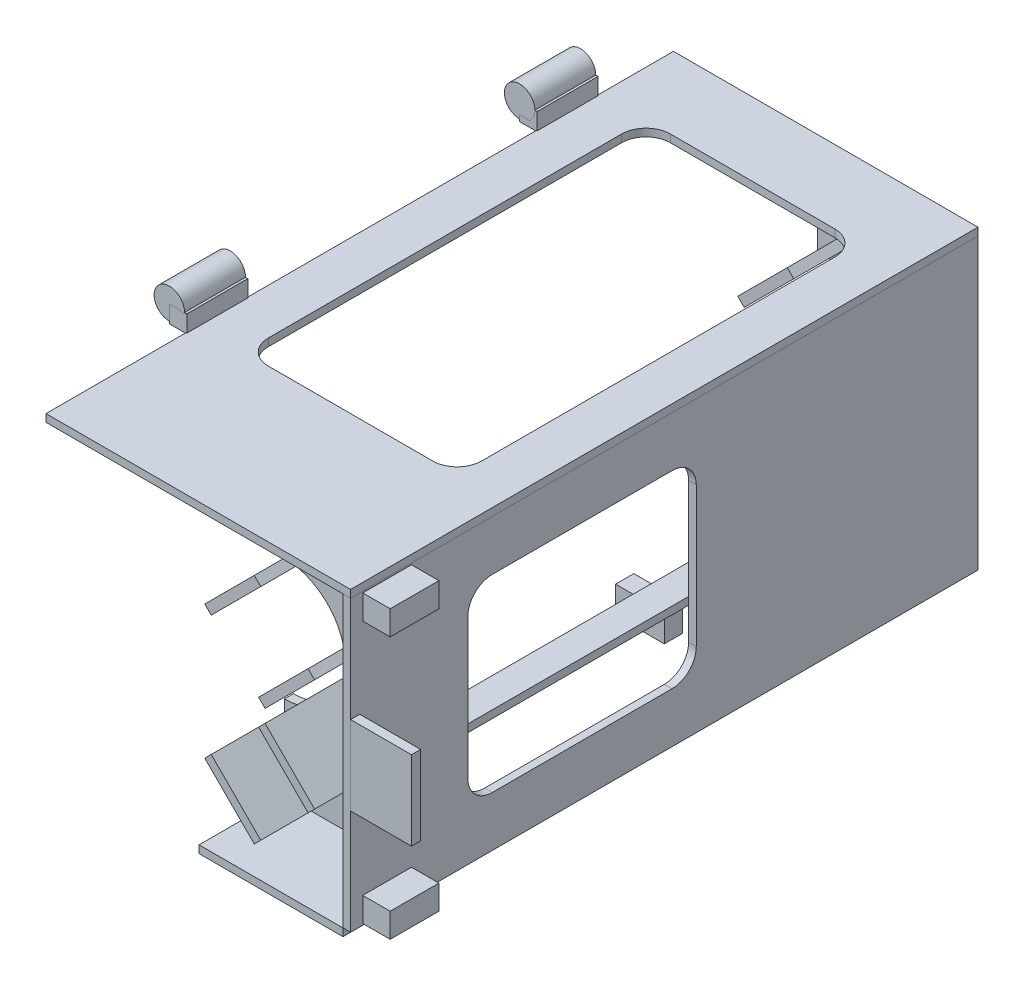
SolidWorks part; units mm, degrees
material "6061-T6 (SS)"
ref_plane "Front Plane" through (0, 0, 0) normal (0, 0, 1) x (1, 0, 0)
ref_plane "Top Plane" through (0, 0, 0) normal (0, 1, 0) x (1, 0, 0)
ref_plane "Right Plane" through (0, 0, 0) normal (1, 0, 0) x (0, 0, -1)
sketch "Extrude sketch 1" plane through (0, 0, 0) normal (0, 0, 1) x (1, 0, 0)
  line L0 (95, -95) -> (95, 95)
  line L1 (95, 95) -> (0.5, 95)
  line L2 (0.5, 95) -> (0.5, 40)
  line L3 (0.5, -40) -> (0.5, -95)
  line L4 (0.5, -95) -> (95, -95)
  arc A0 (0.5, 40) -> (0.5, -40) centre (0.5, 0) cw
  dimension "D1" = 40
  dimension "D2" = 94.5
  dimension "D3" = 95
extrude "Extrude 1" add sketch "Extrude sketch 1" along normal blind 6 from offset 180 separate body
sketch "Extrude sketch 2" plane through (0, 0, 0) normal (0, 0, 1) x (1, 0, 0)
  line L0 (8.4853, 39.598) -> (41.0122, 72.1249)
  line L1 (41.0122, 72.1249) -> (36.7696, 76.3675)
  line L2 (36.7696, 76.3675) -> (4.2426, 43.8406)
  line L3 (4.2426, 43.8406) -> (8.4853, 39.598)
  dimension "D1" = 4.2426
  dimension "D2" = 32.5269
  dimension "D3" = 4.2426
extrude "Extrude 2" add sketch "Extrude sketch 2" along normal blind 56 from offset 186 separate body
sketch "Extrude sketch 3" plane through (0, 0, 0) normal (0, 0, 1) x (1, 0, 0)
  line L0 (72.1249, 41.0122) -> (39.598, 8.4853)
  line L1 (39.598, 8.4853) -> (43.8406, 4.2426)
  line L2 (43.8406, 4.2426) -> (76.3675, 36.7696)
  line L3 (76.3675, 36.7696) -> (72.1249, 41.0122)
  dimension "D1" = 4.2426
  dimension "D2" = 32.5269
  dimension "D3" = 4.2426
extrude "Extrude 3" add sketch "Extrude sketch 3" along normal blind 56 from offset 186 separate body
sketch "Extrude sketch 4" plane through (0, 0, 0) normal (0, 0, 1) x (1, 0, 0)
  line L0 (39.598, -8.4853) -> (72.1249, -41.0122)
  line L1 (72.1249, -41.0122) -> (76.3675, -36.7696)
  line L2 (76.3675, -36.7696) -> (43.8406, -4.2426)
  line L3 (43.8406, -4.2426) -> (39.598, -8.4853)
  dimension "D1" = 4.2426
  dimension "D2" = 32.5269
  dimension "D3" = 4.2426
extrude "Extrude 4" add sketch "Extrude sketch 4" along normal blind 56 from offset 186 separate body
sketch "Extrude sketch 5" plane through (0, 0, 0) normal (0, 0, 1) x (1, 0, 0)
  line L0 (41.0122, -72.1249) -> (8.4853, -39.598)
  line L1 (8.4853, -39.598) -> (4.2426, -43.8406)
  line L2 (4.2426, -43.8406) -> (36.7696, -76.3675)
  line L3 (36.7696, -76.3675) -> (41.0122, -72.1249)
  dimension "D1" = 4.2426
  dimension "D2" = 32.5269
  dimension "D3" = 4.2426
extrude "Extrude 5" add sketch "Extrude sketch 5" along normal blind 56 from offset 186 separate body
sketch "Extrude sketch 6" plane through (0, 0, 0) normal (0, 0, 1) x (1, 0, 0)
  line L0 (95, -95) -> (95, 95)
  line L1 (95, 95) -> (0.5, 95)
  line L2 (0.5, 95) -> (0.5, 40)
  line L3 (0.5, -40) -> (0.5, -95)
  line L4 (0.5, -95) -> (95, -95)
  arc A0 (0.5, 40) -> (0.5, -40) centre (0.5, 0) cw
  dimension "D1" = 40
  dimension "D2" = 94.5
  dimension "D3" = 95
extrude "Extrude 6" add sketch "Extrude sketch 6" along normal blind 6 from offset 530 separate body
sketch "Extrude sketch 7" plane through (0, 0, 0) normal (0, 0, 1) x (1, 0, 0)
  line L0 (8.4853, 39.598) -> (41.0122, 72.1249)
  line L1 (41.0122, 72.1249) -> (36.7696, 76.3675)
  line L2 (36.7696, 76.3675) -> (4.2426, 43.8406)
  line L3 (4.2426, 43.8406) -> (8.4853, 39.598)
  dimension "D1" = 4.2426
  dimension "D2" = 32.5269
  dimension "D3" = 4.2426
extrude "Extrude 7" add sketch "Extrude sketch 7" along normal blind 56 from offset 536 separate body
sketch "Extrude sketch 8" plane through (0, 0, 0) normal (0, 0, 1) x (1, 0, 0)
  line L0 (72.1249, 41.0122) -> (39.598, 8.4853)
  line L1 (39.598, 8.4853) -> (43.8406, 4.2426)
  line L2 (43.8406, 4.2426) -> (76.3675, 36.7696)
  line L3 (76.3675, 36.7696) -> (72.1249, 41.0122)
  dimension "D1" = 4.2426
  dimension "D2" = 32.5269
  dimension "D3" = 4.2426
extrude "Extrude 8" add sketch "Extrude sketch 8" along normal blind 56 from offset 536 separate body
sketch "Extrude sketch 9" plane through (0, 0, 0) normal (0, 0, 1) x (1, 0, 0)
  line L0 (39.598, -8.4853) -> (72.1249, -41.0122)
  line L1 (72.1249, -41.0122) -> (76.3675, -36.7696)
  line L2 (76.3675, -36.7696) -> (43.8406, -4.2426)
  line L3 (43.8406, -4.2426) -> (39.598, -8.4853)
  dimension "D1" = 4.2426
  dimension "D2" = 32.5269
  dimension "D3" = 4.2426
extrude "Extrude 9" add sketch "Extrude sketch 9" along normal blind 56 from offset 536 separate body
sketch "Extrude sketch 10" plane through (0, 0, 0) normal (0, 0, 1) x (1, 0, 0)
  line L0 (41.0122, -72.1249) -> (8.4853, -39.598)
  line L1 (8.4853, -39.598) -> (4.2426, -43.8406)
  line L2 (4.2426, -43.8406) -> (36.7696, -76.3675)
  line L3 (36.7696, -76.3675) -> (41.0122, -72.1249)
  dimension "D1" = 4.2426
  dimension "D2" = 32.5269
  dimension "D3" = 4.2426
extrude "Extrude 10" add sketch "Extrude sketch 10" along normal blind 56 from offset 536 separate body
sketch "Extrude sketch 11" plane through (0, 0, 0) normal (1, 0, 0) x (0, 0, -1)
  line L0 (-180, 95) -> (-592, 95)
  line L1 (-592, 95) -> (-592, -95)
  line L2 (-592, -95) -> (-180, -95)
  line L3 (-180, -95) -> (-180, 95)
  line L4 (-381, 62) -> (-499, 62)
  line L5 (-515, 46) -> (-515, -46)
  line L6 (-499, -62) -> (-381, -62)
  line L7 (-365, -46) -> (-365, 46)
  arc A0 (-499, 62) -> (-515, 46) centre (-499, 46) ccw
  arc A1 (-515, -46) -> (-499, -62) centre (-499, -46) ccw
  arc A2 (-381, -62) -> (-365, -46) centre (-381, -46) ccw
  arc A3 (-365, 46) -> (-381, 62) centre (-381, 46) ccw
  dimension "D1" = 16
  dimension "D2" = 185
  dimension "D3" = 335
  dimension "D4" = 412
  dimension "D5" = 33
  dimension "D6" = 157
  dimension "D7" = 190
extrude "Extrude 11" add sketch "Extrude sketch 11" along normal blind 5 from offset 95 separate body
sketch "Extrude sketch 12" plane through (0, 0, 0) normal (0, 1, 0) x (1, 0, 0)
  line L0 (100, -180) -> (100, -592)
  line L1 (100, -592) -> (-100, -592)
  line L2 (-100, -592) -> (-100, -180)
  line L3 (-100, -180) -> (100, -180)
  line L4 (70, -244) -> (70, -476)
  line L5 (54, -492) -> (-54, -492)
  line L6 (-70, -476) -> (-70, -244)
  line L7 (-54, -228) -> (54, -228)
  arc A0 (70, -476) -> (54, -492) centre (54, -476) cw
  arc A1 (-54, -492) -> (-70, -476) centre (-54, -476) cw
  arc A2 (-70, -244) -> (-54, -228) centre (-54, -244) cw
  arc A3 (54, -228) -> (70, -244) centre (54, -244) cw
  dimension "D1" = 16
  dimension "D2" = 30
  dimension "D3" = 170
  dimension "D4" = 200
  dimension "D5" = 48
  dimension "D6" = 312
  dimension "D7" = 412
extrude "Extrude 12" add sketch "Extrude sketch 12" along normal blind 5 from offset 95 separate body
sketch "Extrude sketch 13" plane through (0, 0, 0) normal (0, 1, 0) x (1, 0, 0)
  line L0 (95, -180) -> (95, -592)
  line L1 (95, -592) -> (0.5, -592)
  line L2 (0.5, -592) -> (0.5, -180)
  line L3 (0.5, -180) -> (95, -180)
  line L4 (76, -242) -> (76, -478)
  line L5 (62, -492) -> (34, -492)
  line L6 (20, -478) -> (20, -242)
  line L7 (34, -228) -> (62, -228)
  arc A0 (76, -478) -> (62, -492) centre (62, -478) cw
  arc A1 (34, -492) -> (20, -478) centre (34, -478) cw
  arc A2 (20, -242) -> (34, -228) centre (34, -242) cw
  arc A3 (62, -228) -> (76, -242) centre (62, -242) cw
  dimension "D1" = 14
  dimension "D2" = 19
  dimension "D3" = 75
  dimension "D4" = 94.5
  dimension "D5" = 48
  dimension "D6" = 312
  dimension "D7" = 412
extrude "Extrude 13" add sketch "Extrude sketch 13" along normal blind 5 from offset 100 separate body
sketch "Extrude sketch 14" plane through (0, 0, 0) normal (0, 0, 1) x (1, 0, 0)
  circle A0 centre (-111, 111) radius 10
  dimension "D1" = 20
extrude "Extrude 14" add sketch "Extrude sketch 14" along normal blind 40 from offset 230 separate body
sketch "Extrude sketch 15" plane through (0, 0, 0) normal (0, 0, 1) x (1, 0, 0)
  line L0 (-111, 99.5) -> (-99.5, 99.5)
  line L1 (-99.5, 99.5) -> (-99.5, 111)
  line L2 (-99.5, 111) -> (-111, 111)
  line L3 (-111, 111) -> (-111, 99.5)
  dimension "D1" = 11.5
extrude "Extrude 15" add sketch "Extrude sketch 15" along normal blind 40 from offset 230 separate body
sketch "Extrude sketch 16" plane through (0, 0, 0) normal (0, 0, 1) x (1, 0, 0)
  circle A0 centre (-111, 111) radius 10
  dimension "D1" = 20
extrude "Extrude 16" add sketch "Extrude sketch 16" along normal blind 40 from offset 460 separate body
sketch "Extrude sketch 17" plane through (0, 0, 0) normal (0, 0, 1) x (1, 0, 0)
  line L0 (-111, 99.5) -> (-99.5, 99.5)
  line L1 (-99.5, 99.5) -> (-99.5, 111)
  line L2 (-99.5, 111) -> (-111, 111)
  line L3 (-111, 111) -> (-111, 99.5)
  dimension "D1" = 11.5
extrude "Extrude 17" add sketch "Extrude sketch 17" along normal blind 40 from offset 460 separate body
sketch "Extrude sketch 18" plane through (0, 0, 0) normal (0, 0, 1) x (1, 0, 0)
  line L0 (-16, -118) -> (16, -118)
  line L1 (16, -118) -> (16, -100)
  line L2 (16, -100) -> (-16, -100)
  line L3 (-16, -100) -> (-16, -118)
  dimension "D1" = 32
  dimension "D2" = 18
extrude "Extrude 18" add sketch "Extrude sketch 18" along normal blind 12 from offset 290 separate body
sketch "Extrude sketch 19" plane through (0, 0, 0) normal (0, 0, 1) x (1, 0, 0)
  line L0 (-16, -118) -> (16, -118)
  line L1 (16, -118) -> (16, -100)
  line L2 (16, -100) -> (-16, -100)
  line L3 (-16, -100) -> (-16, -118)
  dimension "D1" = 32
  dimension "D2" = 18
extrude "Extrude 19" add sketch "Extrude sketch 19" along normal blind 12 from offset 450 separate body
sketch "Extrude sketch 20" plane through (0, 0, 0) normal (0, 0, 1) x (1, 0, 0)
  line L0 (140, -26) -> (140, 26)
  line L1 (140, 26) -> (100, 26)
  line L2 (100, 26) -> (100, -26)
  line L3 (100, -26) -> (140, -26)
  dimension "D1" = 40
  dimension "D2" = 52
extrude "Extrude 20" add sketch "Extrude sketch 20" along normal blind 6 from offset 586 separate body
sketch "Extrude sketch 21" plane through (0, 0, 0) normal (0, 0, 1) x (1, 0, 0)
  line L0 (100, 78) -> (118, 78)
  line L1 (118, 78) -> (118, 94)
  line L2 (118, 94) -> (100, 94)
  line L3 (100, 94) -> (100, 78)
  dimension "D1" = 18
  dimension "D2" = 16
extrude "Extrude 21" add sketch "Extrude sketch 21" along normal blind 32 from offset 552 separate body
sketch "Extrude sketch 22" plane through (0, 0, 0) normal (0, 0, 1) x (1, 0, 0)
  line L0 (100, -94) -> (118, -94)
  line L1 (118, -94) -> (118, -78)
  line L2 (118, -78) -> (100, -78)
  line L3 (100, -78) -> (100, -94)
  dimension "D1" = 18
  dimension "D2" = 16
extrude "Extrude 22" add sketch "Extrude sketch 22" along normal blind 32 from offset 552 separate body
